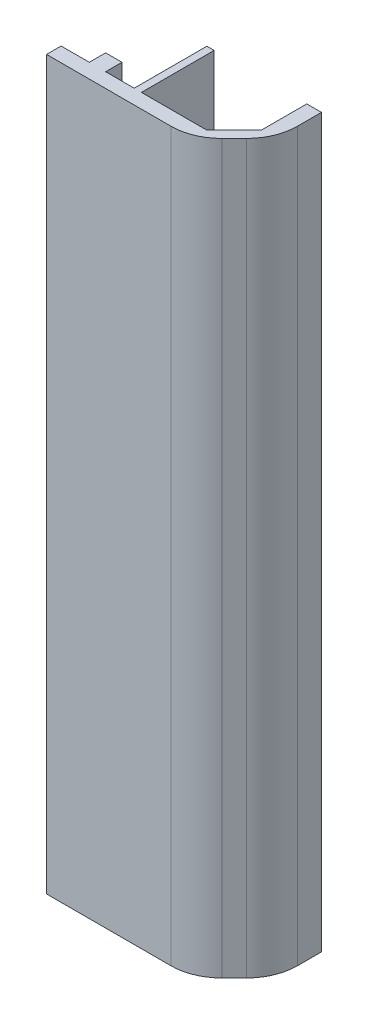
SolidWorks part; units mm, degrees
ref_plane "前基準面" through (0, 0, 0) normal (0, 0, 1) x (1, 0, 0)
ref_plane "上基準面" through (0, 0, 0) normal (0, 1, 0) x (1, 0, 0)
ref_plane "右基準面" through (0, 0, 0) normal (1, 0, 0) x (0, 0, -1)
sketch "草圖1" plane through (0, 0, 0) normal (0, 1, 0) x (1, 0, 0)
  line L0 (-27.5017, 6.8593) -> (-23.0017, 6.8593)
  line L1 (-23.0017, 6.8593) -> (-23.0017, 2.3593)
  line L2 (-23.0017, 2.3593) -> (4.7483, 2.3593)
  line L3 (4.7483, 2.3593) -> (12.3316, 9.9426)
  line L4 (12.3316, 9.9426) -> (12.3316, 22.3593)
  line L5 (-27.5017, 6.8593) -> (-27.5017, 2.3593)
  line L6 (-27.5017, 2.3593) -> (-35.2517, 2.3593)
  line L7 (-35.2517, 2.3593) -> (-35.2517, -1.6407)
  line L8 (-35.2517, -1.6407) -> (4.7783, -1.6407)
  line L12 (4.7783, -1.6407) -> (16.3616, 9.9426)
  line L13 (12.3316, 22.3593) -> (16.3616, 22.3593)
  line L14 (16.3616, 22.3593) -> (16.3616, 9.9426)
  dimension "D1" = 4.5
  dimension "D2" = 4.5
  dimension "D3" = 4
  dimension "D4" = 4
  dimension "D5" = 7.75
  dimension "D6" = 27.75
  dimension "D7" = 20
extrude "填料-伸長1" add sketch "草圖1" along normal blind 200
fillet "圓角1" radius 14 2 edges at (4.7783, 100, 1.6407) (16.3616, 100, -9.9426)
sketch "草圖2" plane through (0, 0, -2.3593) normal (0, 0, -1) x (-1, 0, 0)
  line L0 (-4.7483, 200) -> (23.0017, 200) construction
  line L1 (13.1517, 200) -> (15.1517, 200)
  line L2 (13.1517, 200) -> (13.1517, 0)
  line L3 (13.1517, 0) -> (15.1517, 0)
  line L4 (15.1517, 200) -> (15.1517, 0)
  line L5 (-4.7483, 0) -> (23.0017, 0) construction
  line L6 (35.2517, 200) -> (35.2517, 0) construction
  dimension "D1" = 20.1
  dimension "D2" = 2
extrude "填料-伸長2" add sketch "草圖2" along normal blind 20
